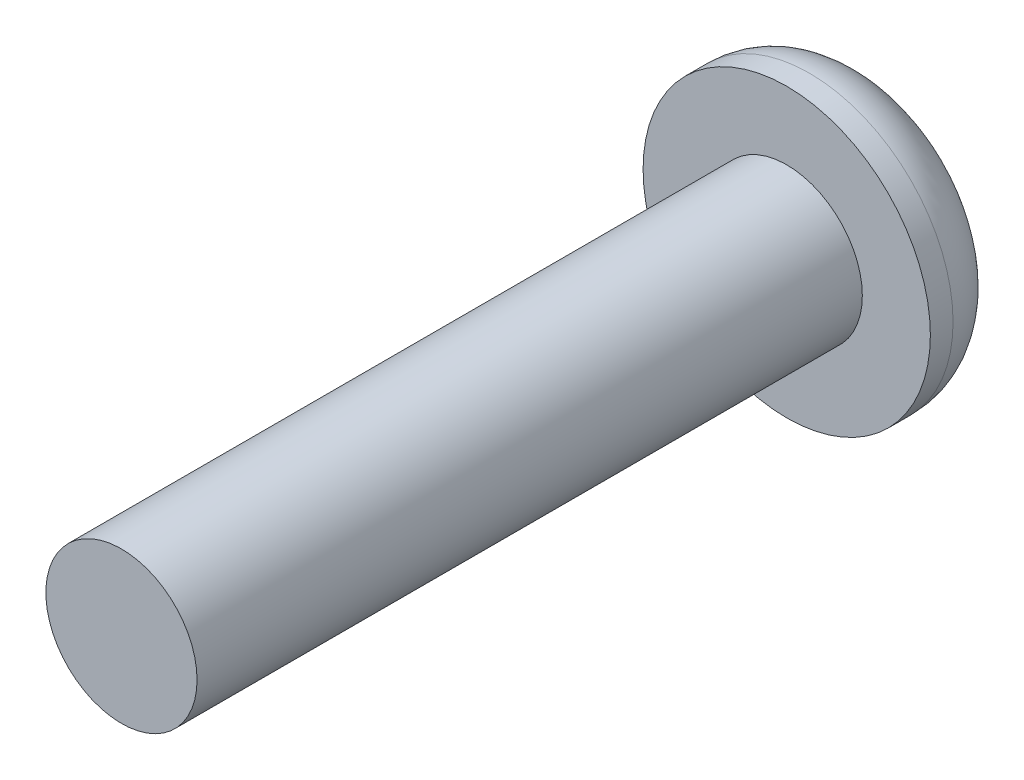
SolidWorks part; units mm, degrees
ref_plane "前视基准面" through (0, 0, 0) normal (0, 0, 1) x (1, 0, 0)
ref_plane "上视基准面" through (0, 0, 0) normal (0, 1, 0) x (1, 0, 0)
ref_plane "右视基准面" through (0, 0, 0) normal (1, 0, 0) x (0, 0, -1)
sketch "草图1" plane through (0, 0, 0) normal (0, 0, 1) x (1, 0, 0)
  circle A0 centre (0, 0) radius 2.5
extrude "凸台-拉伸1" add sketch "草图1" along normal blind 22
sketch "草图2" plane through (0, 0, 0) normal (0, 0, -1) x (-1, 0, 0)
  circle A0 centre (0, 0) radius 4.75
extrude "凸台-拉伸2" add sketch "草图2" along normal blind 2.75
fillet "圆角1" radius 2 1 edges at (-4.75, 0, -2.75)
